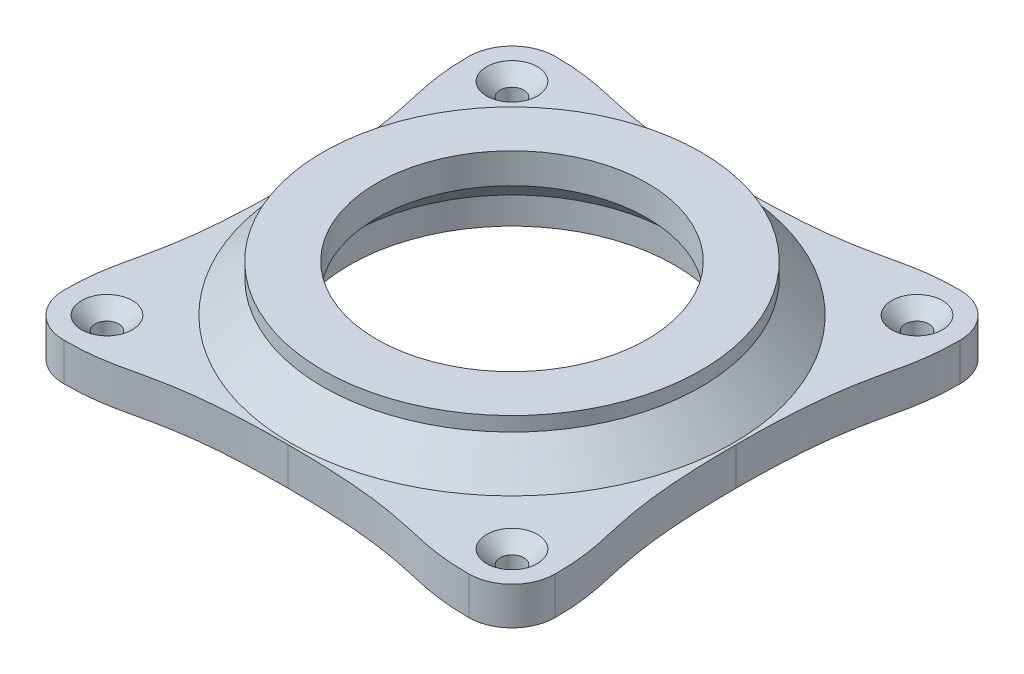
SolidWorks part; units mm, degrees
ref_plane "Front Plane" through (0, 0, 0) normal (0, 0, 1) x (1, 0, 0)
ref_plane "Top Plane" through (0, 0, 0) normal (0, 1, 0) x (1, 0, 0)
ref_plane "Right Plane" through (0, 0, 0) normal (1, 0, 0) x (0, 0, -1)
sketch "Sketch1" plane through (0, 0, 0) normal (0, 1, 0) x (1, 0, 0)
  line L0 (0, 75) -> (75, 0) construction
  line L1 (0, 0) -> (75, 0) construction
  line L2 (0, 0) -> (0, 75) construction
  line L3 (0, 75) -> (75, 75) construction
  line L4 (75, 0) -> (75, 75) construction
  line L5 (0, 75) -> (0, 93.0382) construction
  line L6 (0, 75) -> (-26.3477, 75) construction
  line L7 (75, 75) -> (75, 94.5096) construction
  line L8 (75, 75) -> (107.0147, 75) construction
  line L9 (37.5, 75) -> (37.5, 96.1148) construction
  line L10 (0, 79) -> (75, 79) construction
  line L11 (75, 83) -> (62.5, 83) construction
  line L12 (0, 83) -> (12.5, 83) construction
  line L13 (12.5, 83) -> (12.5, 79) construction
  line L14 (12.5, 79) -> (37.5, 79) construction
  line L15 (62.5, 83) -> (62.5, 79) construction
  line L16 (62.5, 79) -> (37.5, 79) construction
  line L17 (83, 0) -> (83, 12.5) construction
  line L18 (83, 75) -> (83, 62.5) construction
  line L19 (83, 62.5) -> (79, 62.5) construction
  line L20 (79, 62.5) -> (79, 37.5) construction
  line L21 (83, 12.5) -> (79, 12.5) construction
  line L22 (79, 12.5) -> (79, 37.5) construction
  line L23 (0, -8) -> (12.5, -8) construction
  line L24 (75, -8) -> (62.5, -8) construction
  line L25 (62.5, -8) -> (62.5, -4) construction
  line L26 (62.5, -4) -> (37.5, -4) construction
  line L27 (12.5, -8) -> (12.5, -4) construction
  line L28 (12.5, -4) -> (37.5, -4) construction
  line L29 (-8, 75) -> (-8, 62.5) construction
  line L30 (-8, 0) -> (-8, 12.5) construction
  line L31 (-8, 12.5) -> (-4, 12.5) construction
  line L32 (-4, 12.5) -> (-4, 37.5) construction
  line L33 (-8, 62.5) -> (-4, 62.5) construction
  line L34 (-4, 62.5) -> (-4, 37.5) construction
  circle A0 centre (0, 75) radius 2.2
  circle A1 centre (75, 75) radius 2.2
  circle A2 centre (75, 0) radius 2.2
  circle A3 centre (0, 0) radius 2.2
  arc A4 (0, 83) -> (-8, 75) centre (0, 75) ccw
  arc A5 (83, 75) -> (75, 83) centre (75, 75) ccw
  arc A6 (83, 75) -> (75, 83) centre (75, 75) ccw
  arc A7 (75, -8) -> (83, 0) centre (75, 0) ccw
  arc A8 (75, -8) -> (83, 0) centre (75, 0) ccw
  arc A9 (-8, 0) -> (0, -8) centre (0, 0) ccw
  arc A10 (-8, 0) -> (0, -8) centre (0, 0) ccw
  arc A11 (0, 83) -> (-8, 75) centre (0, 75) ccw
  circle A12 centre (37.5, 37.5) radius 25.05
  spline S0 degree 3 poles (0, 83) (12.5, 83) (12.5, 79) (37.5, 79) knots 0 0 0 0 1 1 1 1
  spline S1 degree 3 poles (75, 83) (62.5, 83) (62.5, 79) (37.5, 79) knots 0 0 0 0 1 1 1 1
  spline S2 degree 3 poles (83, 75) (83, 62.5) (79, 62.5) (79, 37.5) knots 0 0 0 0 1 1 1 1
  spline S3 degree 3 poles (83, 0) (83, 12.5) (79, 12.5) (79, 37.5) knots 0 0 0 0 1 1 1 1
  spline S4 degree 3 poles (75, -8) (62.5, -8) (62.5, -4) (37.5, -4) knots 0 0 0 0 1 1 1 1
  spline S5 degree 3 poles (0, -8) (12.5, -8) (12.5, -4) (37.5, -4) knots 0 0 0 0 1 1 1 1
  spline S6 degree 3 poles (-8, 0) (-8, 12.5) (-4, 12.5) (-4, 37.5) knots 0 0 0 0 1 1 1 1
  spline S7 degree 3 poles (-8, 75) (-8, 62.5) (-4, 62.5) (-4, 37.5) knots 0 0 0 0 1 1 1 1
  point P25 (37.5, 37.5)
  point P63 (37.5, 37.5)
  dimension "D2" = 4.4
  dimension "D3" = 8
  dimension "D4" = 4
  dimension "D6" = 50.1
  dimension "D1" = 75
  dimension "D5" = 25
  dimension "D7" = 4
extrude "Boss-Extrude1" add sketch "Sketch1" along normal blind 7 contours A4 S7 S6 A9 S5 S4 A7 S3 S2 A5 S1 S0 A0 A1 A2 A3
sketch "Sketch5" plane through (0, 0, 0) normal (0, -1, 0) x (1, 0, 0)
  circle A0 centre (37.5, -37.5) radius 25.05 construction
  circle A1 centre (37.5, -37.5) radius 25.05
  circle A2 centre (37.5, -37.5) radius 30.1
  dimension "D1" = 60.2
sketch "Sketch6" plane through (0, 7, 0) normal (0, 1, 0) x (1, 0, 0)
  circle A0 centre (37.5, 37.5) radius 25.05 construction
  circle A1 centre (37.5, 37.5) radius 25.05
  circle A2 centre (37.5, 37.5) radius 35
  dimension "D1" = 70
extrude "Boss-Extrude4" add sketch "Sketch6" along normal blind 7
chamfer "Chamfer1" distance 2.5 angle 45 4 edges at (0, 7, -72.8) (0, 7, 2.2) (75, 7, 2.2) (75, 7, -72.8)
chamfer "Chamfer2" distance 6 angle 45 1 edges at (37.5, 7, -2.5)
ref_plane "Plane1" through (0, 0, -37.5) normal (0, 0, 1) x (1, 0, 0)
sketch "Sketch7" plane through (0, 0, -37.5) normal (0, 0, 1) x (1, 0, 0)
  line L0 (72.5, 14) -> (62.55, 14)
  line L1 (12.45, 14) -> (2.5, 14)
  line L2 (12.45, 14) -> (2.5, 14)
  line L3 (72.5, 14) -> (62.55, 14)
  line L4 (-3.5, 7) -> (2.5, 13)
  line L5 (72.5, 13) -> (78.5, 7)
  line L6 (72.5, 13) -> (78.5, 7)
  line L7 (-3.5, 7) -> (2.5, 13)
  line L8 (2.5, 13) -> (2.5, 14)
  line L9 (72.5, 14) -> (72.5, 13)
  line L10 (72.5, 14) -> (72.5, 13)
  line L11 (72.5, 14) -> (72.5, 13)
  line L12 (79, 7) -> (78.5, 7)
  line L13 (-3.5, 7) -> (-4, 7)
  line L14 (-3.5, 7) -> (-4, 7)
  line L15 (79, 7) -> (78.5, 7)
  line L16 (79, 7) -> (79, 0)
  line L17 (79, 7) -> (79, 0)
  line L18 (12.45, 0) -> (12.45, 14)
  line L19 (62.55, 14) -> (62.55, 0)
  line L20 (62.55, 14) -> (62.55, 0)
  line L21 (12.45, 0) -> (12.45, 14)
  line L22 (79, 0) -> (62.55, 0)
  line L23 (12.45, 0) -> (-4, 0)
  line L24 (12.45, 0) -> (-4, 0)
  line L25 (79, 0) -> (62.55, 0)
  line L26 (37.5, 0) -> (37.5, 67.5356) construction
  line L27 (7.4, 0) -> (67.6, 0) construction
  line L28 (7.4, 0) -> (67.6, 0)
  line L29 (67.6, 0) -> (67.6, 5)
  line L30 (67.6, 5) -> (62.55, 10.05)
  line L31 (2.5, 13) -> (2.5, 14)
  dimension "D1" = 45
  dimension "D2" = 5
revolve "Cut-Revolve1" cut sketch "Sketch7" angle 360 about L26
ref_plane "Plane2" through (0, 10.05, 0) normal (0, 1, 0) x (1, 0, 0)
sketch "Sketch8" plane through (0, 14, 0) normal (0, 1, 0) x (1, 0, 0)
  circle A0 centre (37.5, 37.5) radius 25.05 construction
  circle A1 centre (37.5, 37.5) radius 35
  circle A3 centre (37.5, 37.5) radius 25.05
  circle A5 centre (37.5, 37.5) radius 35
  dimension "D1" = 0
extrude "Boss-Extrude8" add sketch "Sketch8" along normal blind 5.6 from surface at -3.95 starting at plane "Plane2"
